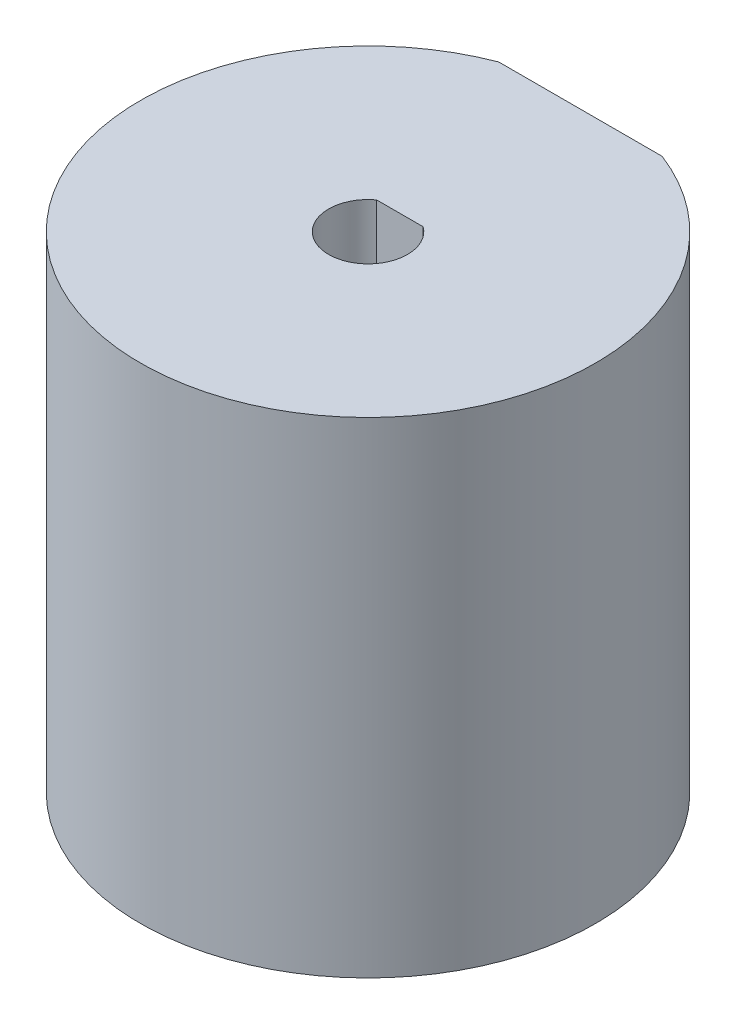
SolidWorks part; units mm, degrees
ref_plane "Front Plane" through (0, 0, 0) normal (0, 0, 1) x (1, 0, 0)
ref_plane "Top Plane" through (0, 0, 0) normal (0, 1, 0) x (1, 0, 0)
ref_plane "Right Plane" through (0, 0, 0) normal (1, 0, 0) x (0, 0, -1)
sketch "Sketch1" plane through (0, 0, 0) normal (0, 1, 0) x (1, 0, 0)
  line L0 (1.5492, 2.15) -> (-1.5492, 2.15)
  line L1 (0, 2) -> (1.5, 2)
  line L2 (1.5, 2) -> (0, 2)
  line L3 (1.5, 2) -> (-1.5, 2) construction
  arc A0 (-1.5, 2) -> (1.5, 2) centre (0, 0) ccw
  arc A1 (-1.5492, 2.15) -> (1.5492, 2.15) centre (0, 0) ccw
  circle A2 centre (0, 0) radius 6
  dimension "D1" = 0.15
extrude "Boss-Extrude1" add sketch "Sketch1" along normal blind 5 contours A2 A1 L0
sketch "Sketch2" plane through (0, 5, 0) normal (0, 1, 0) x (1, 0, 0)
  line L0 (1.5264, 2.08) -> (-1.5264, 2.08)
  line L1 (1.5492, 2.15) -> (-1.5492, 2.15)
  line L2 (1.5492, 2.15) -> (-1.5492, 2.15)
  arc A0 (-1.5264, 2.08) -> (1.5264, 2.08) centre (0, 0) ccw
  arc A1 (-1.5492, 2.15) -> (1.5492, 2.15) centre (0, 0) ccw
  arc A2 (-1.5492, 2.15) -> (1.5492, 2.15) centre (0, 0) ccw
  dimension "D1" = 0
  dimension "D2" = 0.07
extrude "Boss-Extrude2" add sketch "Sketch2" against normal up to surface (5 mm away) up to face at (0, 0, 0.25)
sketch "Sketch3" plane through (0, 5, 0) normal (0, 1, 0) x (1, 0, 0)
  line L3 (1.533, 2.1) -> (-1.533, 2.1)
  line L4 (1.533, 2.1) -> (-1.533, 2.1)
  arc A2 (-1.533, 2.1) -> (1.533, 2.1) centre (0, 0) ccw
  arc A3 (-1.533, 2.1) -> (1.533, 2.1) centre (0, 0) ccw
  dimension "D1" = 0.02
extrude "Cut-Extrude1" cut sketch "Sketch3" against normal blind 5
sketch "Sketch4" plane through (0, 5, 0) normal (0, 1, 0) x (1, 0, 0)
  line L0 (1.533, 2.1) -> (-1.533, 2.1) construction
  line L1 (1.533, 2.1) -> (-1.533, 2.1)
  arc A0 (-1.533, 2.1) -> (1.533, 2.1) centre (0, 0) ccw construction
  arc A1 (-1.533, 2.1) -> (1.533, 2.1) centre (0, 0) ccw
  circle A2 centre (0, 0) radius 15
extrude "Boss-Extrude3" add sketch "Sketch4" against normal blind 15
sketch "Sketch5" plane through (0, -10, 0) normal (0, -1, 0) x (1, 0, 0)
  circle A0 centre (0, 0) radius 15
extrude "Boss-Extrude4" add sketch "Sketch5" along normal blind 2
sketch "Sketch6" plane through (0, -12, 0) normal (0, -1, 0) x (1, 0, 0)
  line L5 (8, 8) -> (-8, 8)
  line L6 (8, 8) -> (8, -8)
  line L7 (8, -8) -> (-8, -8)
  line L8 (-8, 8) -> (-8, -8)
  circle A2 centre (0, 0) radius 15
  circle A3 centre (0, 0) radius 15
  dimension "D1" = 0
extrude "Boss-Extrude5" add sketch "Sketch6" along normal blind 15
sketch "Sketch7" plane through (0, 5, 0) normal (0, 1, 0) x (1, 0, 0)
  line L0 (0, 15) -> (0, 14)
  line L1 (0, 14) -> (-8.6763, 14)
  line L2 (-8.6763, 14) -> (10.7687, 14)
  circle A0 centre (0, 0) radius 15 construction
  circle A2 centre (0, 0) radius 15
  circle A3 centre (0, 0) radius 15
  circle M7 centre (0, 0) radius 15
  dimension "D1" = 0
extrude "Cut-Extrude2" cut sketch "Sketch7" against normal blind 51 contours L1 L0 M7 | L0 L2 M7
sketch "Sketch8" plane through (0, 0, -2.1) normal (0, 0, 1) x (1, 0, 0)
  line L0 (-1.533, -2.5) -> (1.533, -2.5)
  line L1 (-1.533, -10) -> (-1.533, 5) construction
  line L2 (1.533, -10) -> (1.533, 5) construction
  circle A0 centre (0, -2.5) radius 1.6
  line M2 (-1.533, 5) -> (-1.533, -10)
  line M4 (1.533, -10) -> (1.533, 5)
extrude "Cut-Extrude5" cut sketch "Sketch8" against normal blind 51 and the other way blind 1 contours A0 M4 | A0 L0 M4 M2 | A0 L0 M2 M4 | A0 M2
sketch "Sketch10" plane through (0, 0, -14) normal (0, 0, -1) x (-1, 0, 0)
  circle A0 centre (0, -2.5) radius 2.6
extrude "Cut-Extrude6" cut sketch "Sketch10" against normal blind 7
